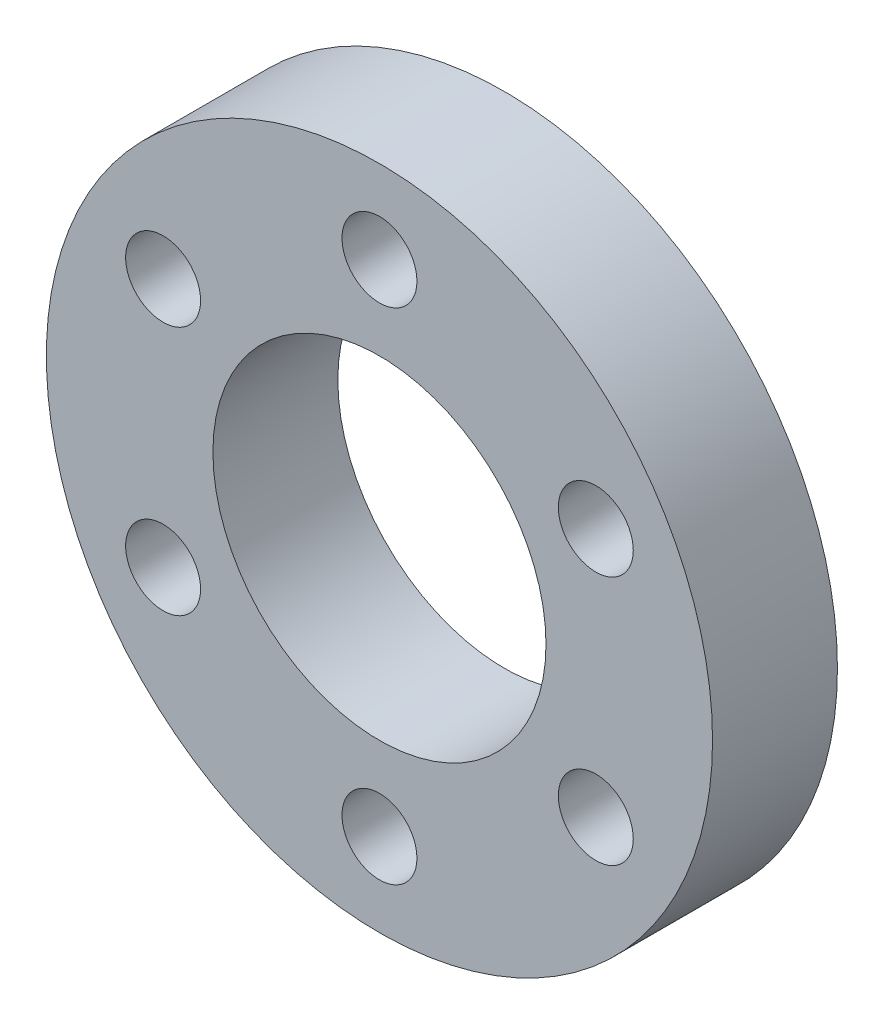
SolidWorks part; units mm, degrees
ref_plane "Plano frontal" through (0, 0, 0) normal (0, 0, 1) x (1, 0, 0)
ref_plane "Plano superior" through (0, 0, 0) normal (0, 1, 0) x (1, 0, 0)
ref_plane "Plano direito" through (0, 0, 0) normal (1, 0, 0) x (0, 0, -1)
sketch "Esboço1" plane through (0, 0, 0) normal (0, 0, 1) x (1, 0, 0)
  circle A0 centre (0, 0) radius 8
  circle A1 centre (0, 0) radius 4
  dimension "D1" = 16
  dimension "D2" = 8
extrude "Ressalto-extrusão1" add sketch "Esboço1" along normal blind 3
sketch "Esboço2" plane through (0, 0, 3) normal (0, 0, 1) x (1, 0, 0)
  circle A0 centre (0, 0) radius 6
  point P3 (0, 6)
  dimension "D1" = 12
hole_wizard "Furo com folga de M1.61" positions "3DSketch1" profile "Esboço3" hole size "M1.6" standard "ISO" end condition through all
sketch3d "3DSketch1"
  point P0 (0, 6, 3)
sketch "Esboço3" plane through (0, 6, 3) normal (1, 0, 0) x (0, -1, 0)
  line L0 (0, 0) -> (0, 3)
  line L1 (0, 3) -> (0.9, 3)
  line L2 (0.9, 3) -> (0.9, 0)
  line L5 (0.9, 0) -> (0, 0)
  line L11 (0, -6.35) -> (0, 107.95) construction
  dimension "Thru Hole Dia." = 1.8
  dimension "Thru Hole Depth" = 3
pattern_circular "PadrãoCircular1" count 6 over 360 about axis through (0, 0, 0) along (0, 0, 1) of "Furo com folga de M1.61"
